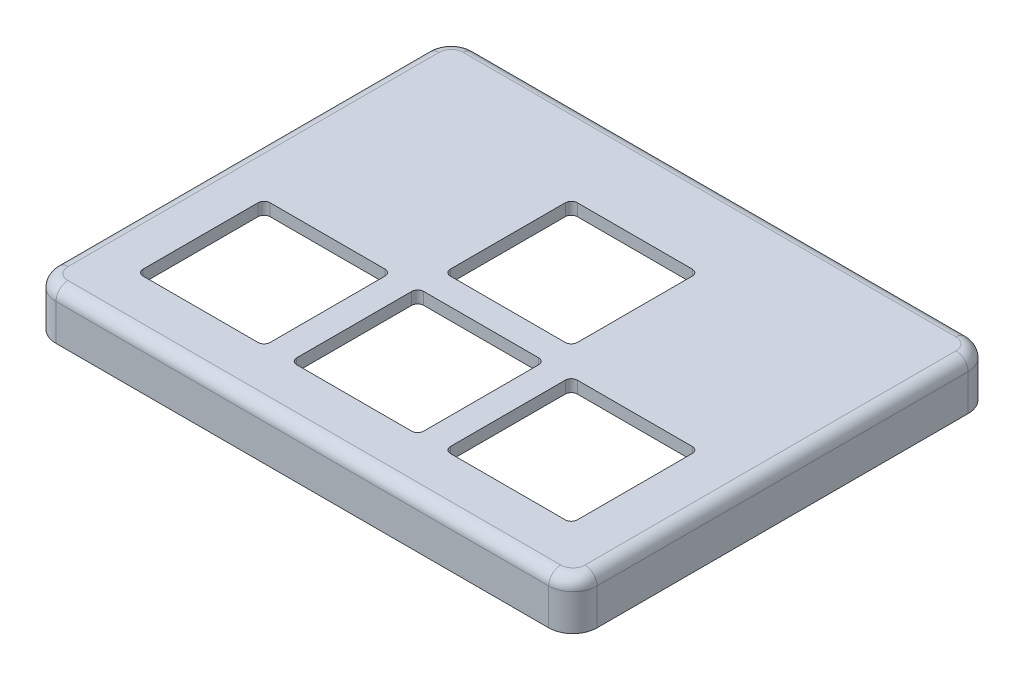
SolidWorks part; units mm, degrees
ref_plane "Front Plane" through (0, 0, 0) normal (0, 0, 1) x (1, 0, 0)
ref_plane "Top Plane" through (0, 0, 0) normal (0, 1, 0) x (1, 0, 0)
ref_plane "Right Plane" through (0, 0, 0) normal (1, 0, 0) x (0, 0, -1)
sketch "Sketch1" plane through (0, 0, 0) normal (0, 1, 0) x (1, 0, 0)
  line L1 (3, 0) -> (64.1, 0)
  line L2 (0, 3) -> (0, 49)
  line L3 (3, 52) -> (64.1, 52)
  line L4 (67.1, 3) -> (67.1, 49)
  arc A0 (3, 0) -> (0, 3) centre (3, 3) cw
  arc A1 (64.1, 0) -> (67.1, 3) centre (64.1, 3) ccw
  arc A2 (64.1, 52) -> (67.1, 49) centre (64.1, 49) cw
  arc A3 (0, 49) -> (3, 52) centre (3, 49) cw
  point P7 (0, 0)
  point P10 (67.1, 0)
  point P13 (67.1, 52)
  dimension "D3" = 3
  dimension "D1" = 67.1
  dimension "D2" = 52
extrude "Boss-Extrude1" add sketch "Sketch1" along normal blind 6
sketch "Sketch2" plane through (0, 0, 0) normal (0, -1, 0) x (-1, 0, 0)
  line L1 (-4.9, 1.9) -> (-62.2, 1.9)
  line L2 (-1.9, 4.9) -> (-1.9, 48.1)
  line L3 (-4.9, 51.1) -> (-62.2, 51.1)
  line L4 (-65.2, 4.9) -> (-65.2, 48.1)
  line L5 (0, 49) -> (0, 3) construction
  line L6 (-3, 0) -> (-64.1, 0) construction
  arc A0 (-62.2, 51.1) -> (-65.2, 48.1) centre (-62.2, 48.1) ccw
  arc A1 (-62.2, 1.9) -> (-65.2, 4.9) centre (-62.2, 4.9) cw
  arc A2 (-4.9, 1.9) -> (-1.9, 4.9) centre (-4.9, 4.9) ccw
  arc A3 (-1.9, 48.1) -> (-4.9, 51.1) centre (-4.9, 48.1) ccw
  point P6 (-65.2, 51.1)
  point P9 (-65.2, 1.9)
  point P14 (-1.9, 51.1)
  dimension "D3" = 3
  dimension "D1" = 1.9
  dimension "D2" = 49.2
  dimension "D4" = 63.3
  dimension "D5" = 1.9
extrude "Cut-Extrude1" cut sketch "Sketch2" against normal blind 4.5
sketch "Sketch3" plane through (0, 6, 0) normal (0, 1, 0) x (1, 0, 0)
  line L0 (33.35, 52) -> (33.35, 0) construction
  line L1 (26.225, 41.43) -> (40.475, 41.43)
  line L2 (25.475, 40.68) -> (25.475, 26.43)
  line L3 (26.225, 25.68) -> (40.475, 25.68)
  line L4 (41.225, 40.68) -> (41.225, 26.43)
  line L5 (7.175, 22.38) -> (21.425, 22.38)
  line L6 (6.425, 21.63) -> (6.425, 7.38)
  line L7 (7.175, 6.63) -> (21.425, 6.63)
  line L8 (22.175, 21.63) -> (22.175, 7.38)
  line L9 (26.225, 22.38) -> (40.475, 22.38)
  line L10 (25.475, 21.63) -> (25.475, 7.38)
  line L11 (26.225, 6.63) -> (40.475, 6.63)
  line L12 (41.225, 21.63) -> (41.225, 7.38)
  line L13 (45.275, 22.38) -> (59.525, 22.38)
  line L14 (44.525, 21.63) -> (44.525, 7.38)
  line L15 (45.275, 6.63) -> (59.525, 6.63)
  line L16 (60.275, 21.63) -> (60.275, 7.38)
  line L18 (3, 0) -> (64.1, 0) construction
  line L24 (0, 49) -> (0, 3) construction
  arc A0 (26.225, 41.43) -> (25.475, 40.68) centre (26.225, 40.68) ccw
  arc A1 (40.475, 41.43) -> (41.225, 40.68) centre (40.475, 40.68) cw
  arc A2 (40.475, 25.68) -> (41.225, 26.43) centre (40.475, 26.43) ccw
  arc A3 (25.475, 26.43) -> (26.225, 25.68) centre (26.225, 26.43) ccw
  arc A4 (59.525, 6.63) -> (60.275, 7.38) centre (59.525, 7.38) ccw
  arc A5 (44.525, 7.38) -> (45.275, 6.63) centre (45.275, 7.38) ccw
  arc A6 (59.525, 22.38) -> (60.275, 21.63) centre (59.525, 21.63) cw
  arc A7 (45.275, 22.38) -> (44.525, 21.63) centre (45.275, 21.63) ccw
  arc A8 (25.475, 7.38) -> (26.225, 6.63) centre (26.225, 7.38) ccw
  arc A9 (40.475, 6.63) -> (41.225, 7.38) centre (40.475, 7.38) ccw
  arc A10 (40.475, 22.38) -> (41.225, 21.63) centre (40.475, 21.63) cw
  arc A11 (26.225, 22.38) -> (25.475, 21.63) centre (26.225, 21.63) ccw
  arc A12 (21.425, 22.38) -> (22.175, 21.63) centre (21.425, 21.63) cw
  arc A13 (21.425, 6.63) -> (22.175, 7.38) centre (21.425, 7.38) ccw
  arc A14 (6.425, 7.38) -> (7.175, 6.63) centre (7.175, 7.38) ccw
  arc A15 (7.175, 22.38) -> (6.425, 21.63) centre (7.175, 21.63) ccw
  point P22 (33.35, 6.63)
  point P53 (6.425, 6.63)
  point P56 (6.425, 22.38)
  dimension "D6" = 0.75
  dimension "D1" = 15.75
  dimension "D2" = 3.3
  dimension "D3" = 3.3
  dimension "D4" = 3.3
  dimension "D5" = 6.63
  dimension "D7" = 33.35
extrude "Cut-Extrude2" cut sketch "Sketch3" against normal blind 1.5
fillet "Fillet1" radius 1.5 8 edges at (66.2213, 6, -51.1213) (67.1, 6, -26) (66.2213, 6, -0.8787) (33.55, 6, 0) (0.8787, 6, -0.8787) (0.8787, 6, -51.1213) (0, 6, -26) (33.55, 6, -52)
sketch "Sketch4" plane through (0, 0, 0) normal (0, -1, 0) x (1, 0, 0)
  line L0 (0.7, -6) -> (1.3, -6)
  line L1 (0.7, -6) -> (0.7, -46)
  line L2 (0.7, -46) -> (1.3, -46)
  line L3 (1.3, -6) -> (1.3, -46)
  line L4 (6.05, -0.7) -> (61.05, -0.7)
  line L5 (6.05, -0.7) -> (6.05, -1.3)
  line L6 (6.05, -1.3) -> (61.05, -1.3)
  line L7 (61.05, -0.7) -> (61.05, -1.3)
  line L8 (65.8, -6) -> (66.4, -6)
  line L9 (65.8, -6) -> (65.8, -46)
  line L10 (65.8, -46) -> (66.4, -46)
  line L11 (66.4, -6) -> (66.4, -46)
  line L12 (0, -26) -> (67.1, -26) construction
  line L13 (33.55, 0) -> (33.55, -52) construction
  line L14 (0, -49) -> (0, -3) construction
  line L15 (67.1, -3) -> (67.1, -49) construction
  line L16 (3, 0) -> (64.1, 0) construction
  line L17 (64.1, -52) -> (3, -52) construction
  line L18 (65.2, -48.1) -> (65.2, -4.9) construction
  line L19 (62.2, -1.9) -> (4.9, -1.9) construction
  line L20 (1.9, -4.9) -> (1.9, -48.1) construction
  point P14 (65.8, -26)
  point P15 (1.3, -26)
  point P18 (33.55, -0.7)
  dimension "D1" = 0.6
  dimension "D2" = 40
  dimension "D3" = 55
  dimension "D4" = 0.6
  dimension "D5" = 0.6
  dimension "D6" = 0.6
extrude "Cut-Extrude3" cut sketch "Sketch4" against normal blind 2.5
